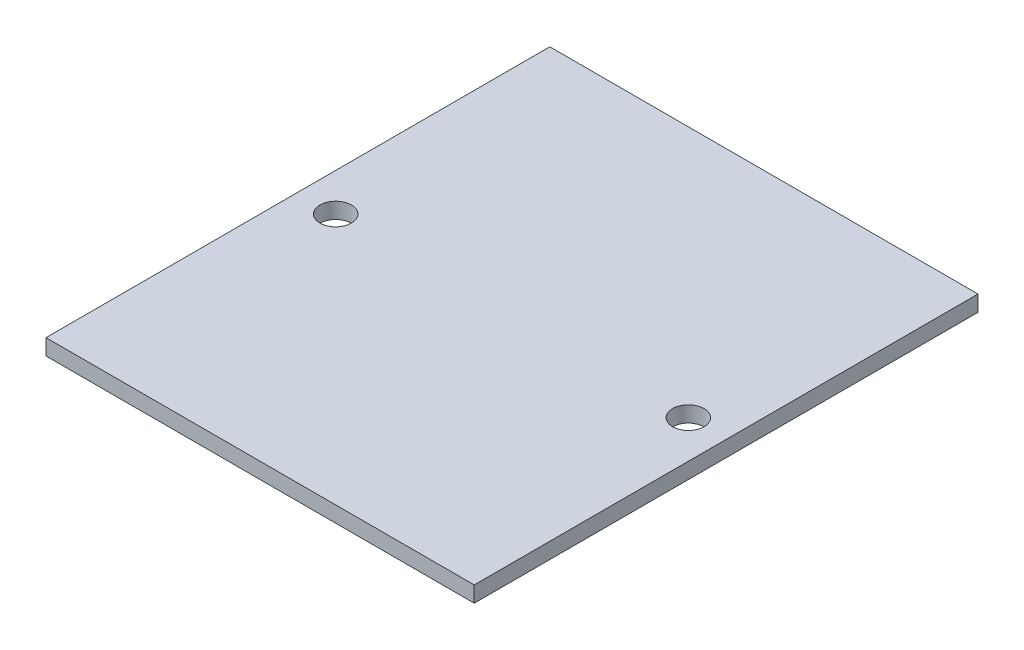
SolidWorks part; units mm, degrees
ref_plane "Front Plane" through (0, 0, 0) normal (0, 0, 1) x (1, 0, 0)
ref_plane "Top Plane" through (0, 0, 0) normal (0, 1, 0) x (1, 0, 0)
ref_plane "Right Plane" through (0, 0, 0) normal (1, 0, 0) x (0, 0, -1)
sketch "Sketch1" plane through (0, 0, 0) normal (0, 1, 0) x (1, 0, 0)
  line L0 (-17.78, 0) -> (17.78, 0) construction
  line L1 (-21.59, -25.4) -> (21.59, -25.4)
  line L2 (-21.59, -25.4) -> (-21.59, 25.4)
  line L3 (-21.59, 25.4) -> (21.59, 25.4)
  line L4 (21.59, -25.4) -> (21.59, 25.4)
  line L5 (-21.59, -25.4) -> (21.59, 25.4) construction
  line L6 (-21.59, 25.4) -> (21.59, -25.4) construction
  circle A0 centre (-17.78, 0) radius 1.5875
  circle A1 centre (17.78, 0) radius 1.5875
  point P0 (0, 0)
  point P10 (-19.645, 0)
  dimension "D3" = 3.175
  dimension "D1" = 43.18
  dimension "D2" = 50.8
  dimension "D4" = 35.56
extrude "Boss-Extrude2" add sketch "Sketch1" along normal blind 1.6002
